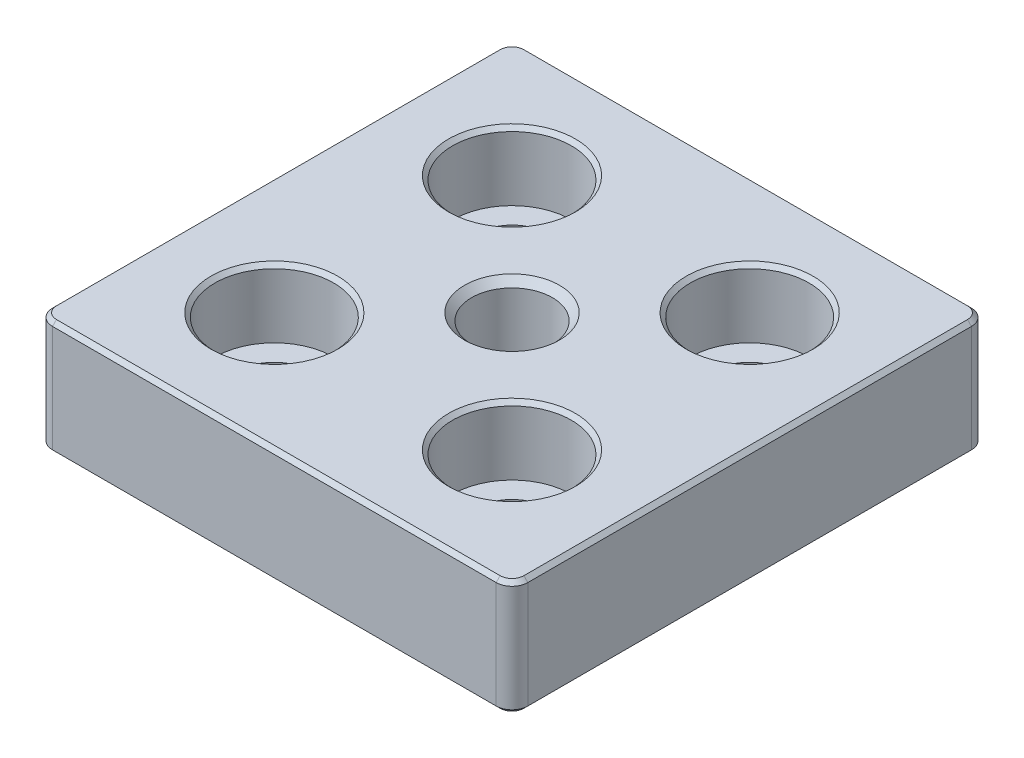
SolidWorks part; units mm, degrees
material "6061 Alloy"
ref_plane "Front Plane" through (0, 0, 0) normal (0, 0, 1) x (1, 0, 0)
ref_plane "Top Plane" through (0, 0, 0) normal (0, 1, 0) x (1, 0, 0)
ref_plane "Right Plane" through (0, 0, 0) normal (1, 0, 0) x (0, 0, -1)
sketch "Sketch1" plane through (0, 0, 0) normal (0, 1, 0) x (1, 0, 0)
  line L1 (30, -30) -> (-30, -30)
  line L2 (30, -30) -> (30, 30)
  line L3 (30, 30) -> (-30, 30)
  line L4 (-30, -30) -> (-30, 30)
  line L5 (30, -30) -> (-30, 30) construction
  line L6 (30, 30) -> (-30, -30) construction
  point P0 (0, 0)
  dimension "D1" = 60
  dimension "D2" = 60
extrude "Boss-Extrude1" add sketch "Sketch1" along normal blind 14.5
hole_wizard "CBORE for M8 Hex Socket Head Cap Screw1" positions "Sketch2" profile "Sketch4" counterbore size "M8" standard "DIN" end condition up to next
sketch "Sketch2" plane through (0, 14.5, 0) normal (0, 1, 0) x (1, 0, 0)
  line L1 (0, 0) -> (0, 30) construction
  line L2 (30, 30) -> (-30, 30) construction
  point P0 (-15, -15)
  point P17 (15, -15)
  point P18 (15, 15)
  point P19 (-15, 15)
  point P20 (-15.5003, -2.0881)
  point P21 (-15.6609, 14.2956)
  point P22 (0, 0)
  point P23 (-10.2301, -14.6184)
  point P24 (0, 0)
  point P25 (-13, -15)
  dimension "D4" = 30
  dimension "D5" = 30
  dimension "D6" = 15
  dimension "D2" = 2
  dimension "D3" = 2
sketch "Sketch4" plane through (-15, 14.5, 15) normal (1, 0, 0) x (0, 0, 1)
  line L0 (0, 0) -> (0, 14.5)
  line L1 (4.5, 14) -> (5, 14.5)
  line L2 (7.5, 8.6) -> (4.5, 8.6)
  line L3 (4.5, 8.6) -> (4.5, 14)
  line L5 (7.5, 8.6) -> (7.5, 0.5)
  line L6 (7.5, 0.5) -> (8, 0)
  line L7 (8, 0) -> (0, 0)
  line L8 (-7.5, 0.5) -> (-8, 0) construction
  line L11 (0, -6.35) -> (0, 107.95) construction
  line L12 (5, 14.5) -> (0, 14.5)
  line L13 (-4.5, 14) -> (-5, 14.5) construction
  dimension "Thru Hole Dia." = 9
  dimension "Thru Hole Depth" = 14.5
  dimension "C'Bore Dia." = 15
  dimension "C'Bore Depth" = 8.6
  dimension "Near C'Sink Dia." = 16
  dimension "Near C'Sink Angle" = 90
  dimension "Far C'Sink Dia." = 10
  dimension "Far C'Sink Angle" = 90
hole_wizard "M12 Tapped Hole1" positions "Sketch5" profile "Sketch7" tap size "M12" standard "DIN" end condition up to next
sketch "Sketch5" plane through (0, 14.5, 0) normal (0, 1, 0) x (1, 0, 0)
  point P0 (0, 0)
cosmetic thread "Hole Thread1" parameters "D2"=12
sketch "Sketch7" plane through (0, 14.5, 0) normal (1, 0, 0) x (0, 0, 1)
  line L0 (0, 0) -> (0, 14.5)
  line L1 (0, 14.5) -> (6, 14.5)
  line L2 (5.1, 13.6) -> (5.1, 0.9)
  line L3 (5.1, 0.9) -> (6, 0)
  line L5 (6, 0) -> (0, 0)
  line L6 (-5.1, 0.9) -> (-6, 0) construction
  line L7 (6, 14.5) -> (5.1, 13.6)
  line L8 (-6, 14.5) -> (-5.1, 13.6) construction
  line L11 (0, -6.35) -> (0, 107.95) construction
  dimension "Thru Tap Drill Dia." = 10.2
  dimension "Thru Tap Drill Depth" = 14.5
  dimension "Near C'Sink Dia." = 12
  dimension "Near C'Sink Angle" = 90
  dimension "Far C'Sink Dia." = 12
  dimension "Far C'Sink Angle" = 90
fillet "Fillet1" radius 2 4 edges at (-30, 7.25, 30) (30, 7.25, 30) (30, 7.25, -30) (-30, 7.25, -30)
chamfer "Chamfer1" distance 0.5 angle 45 16 edges at (-29.4142, 14.5, -29.4142) (0, 14.5, -30) (29.4142, 14.5, -29.4142) (30, 14.5, 0) (29.4142, 14.5, 29.4142) (0, 14.5, 30) (-29.4142, 14.5, 29.4142) (-30, 14.5, 0) (29.4142, 0, 29.4142) (30, 0, 0) (29.4142, 0, -29.4142) (0, 0, -30) (-29.4142, 0, -29.4142) (-30, 0, 0) (-29.4142, 0, 29.4142) (0, 0, 30)
